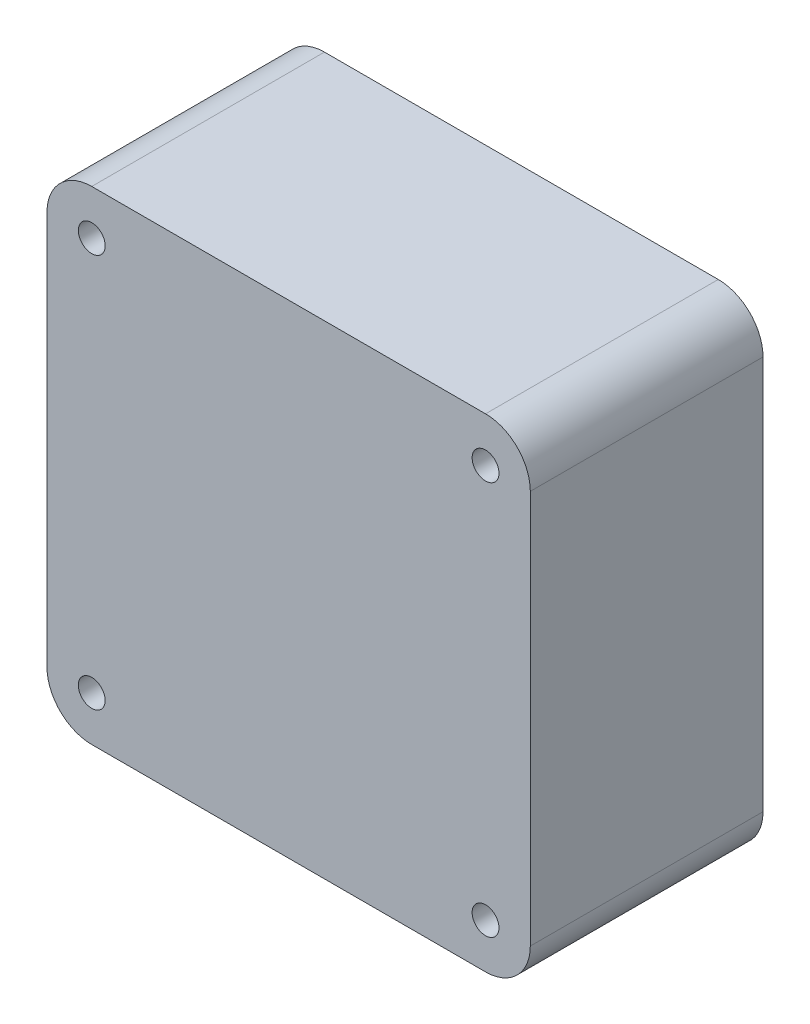
SolidWorks part; units mm, degrees
ref_plane "Alzado" through (0, 0, 0) normal (0, 0, 1) x (1, 0, 0)
ref_plane "Planta" through (0, 0, 0) normal (0, 1, 0) x (1, 0, 0)
ref_plane "Vista lateral" through (0, 0, 0) normal (1, 0, 0) x (0, 0, -1)
sketch "Croquis1" plane through (0, 0, 0) normal (0, 0, 1) x (1, 0, 0)
  line L1 (27, -27) -> (-27, -27)
  line L2 (27, -27) -> (27, 27)
  line L3 (27, 27) -> (-27, 27)
  line L4 (-27, -27) -> (-27, 27)
  line L5 (27, -27) -> (-27, 27) construction
  line L6 (27, 27) -> (-27, -27) construction
  point P0 (0, 0)
  dimension "D1" = 54
  dimension "D2" = 54
extrude "Saliente-Extruir1" add sketch "Croquis1" along normal blind 26
fillet "Redondeo1" radius 5 4 edges at (-27, -27, 13) (27, -27, 13) (27, 27, 13) (-27, 27, 13)
sketch "Croquis2" plane through (0, 0, 26) normal (0, 0, 1) x (1, 0, 0)
  line L1 (22, -22) -> (-22, -22) construction
  line L2 (22, -22) -> (22, 22) construction
  line L3 (22, 22) -> (-22, 22) construction
  line L4 (-22, -22) -> (-22, 22) construction
  line L5 (22, -22) -> (-22, 22) construction
  line L6 (22, 22) -> (-22, -22) construction
  circle A0 centre (-22, 22) radius 1.5
  circle A1 centre (22, 22) radius 1.5
  circle A2 centre (22, -22) radius 1.5
  circle A3 centre (-22, -22) radius 1.5
  point P0 (0, 0)
  dimension "D3" = 3
  dimension "D1" = 44
  dimension "D2" = 44
extrude "Cortar-Extruir1" cut sketch "Croquis2" against normal through all
